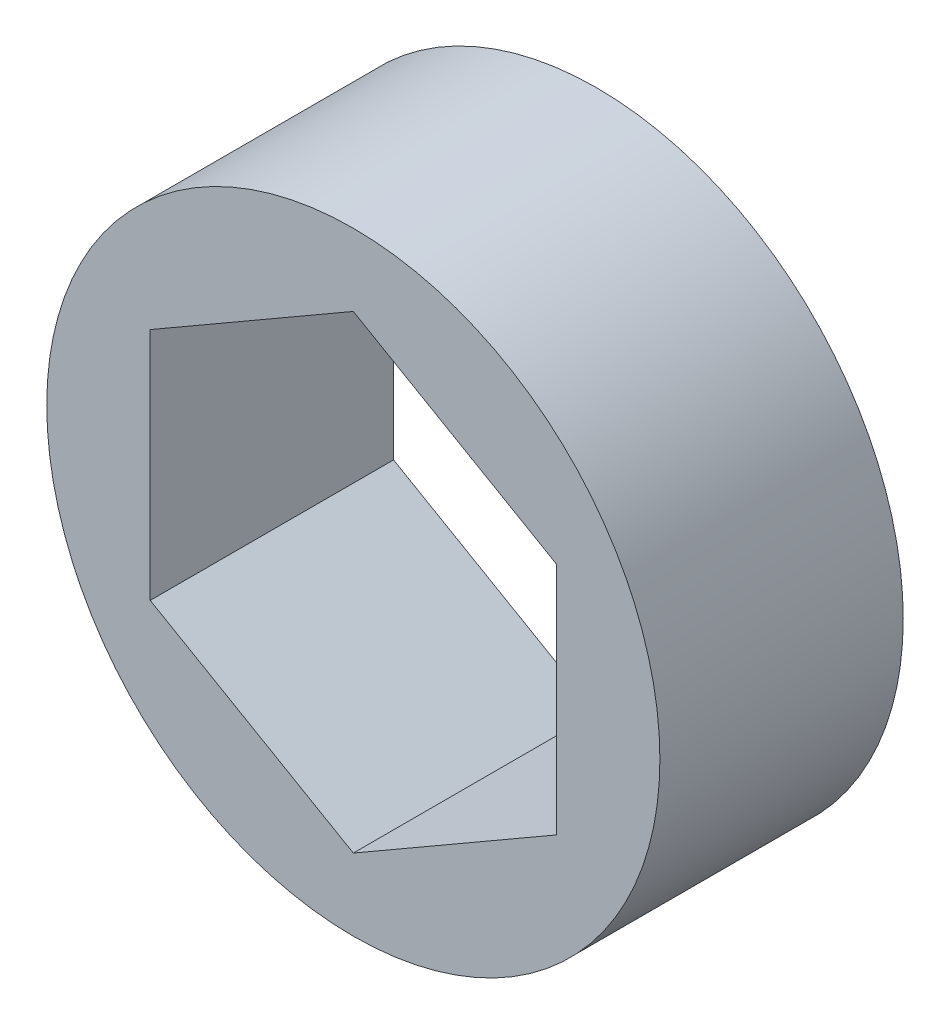
SolidWorks part; units mm, degrees
material "Nylon 101"
ref_plane "Front Plane" through (0, 0, 0) normal (0, 0, 1) x (1, 0, 0)
ref_plane "Top Plane" through (0, 0, 0) normal (0, 1, 0) x (1, 0, 0)
ref_plane "Right Plane" through (0, 0, 0) normal (1, 0, 0) x (0, 0, -1)
sketch "Sketch1" plane through (0, 0, 0) normal (0, 0, 1) x (1, 0, 0)
  line L1 (6.731, 3.8861) -> (0, 7.7723)
  line L2 (0, 7.7723) -> (-6.731, 3.8861)
  line L3 (-6.731, 3.8861) -> (-6.731, -3.8861)
  line L4 (-6.731, -3.8861) -> (0, -7.7723)
  line L5 (0, -7.7723) -> (6.731, -3.8861)
  line L6 (6.731, -3.8861) -> (6.731, 3.8861)
  circle A0 centre (0, 0) radius 6.731 construction
  circle A1 centre (0, 0) radius 10.16
  dimension "D1" = 13.462
  dimension "D2" = 20.32
extrude "Boss-Extrude1" add sketch "Sketch1" along normal blind 8.0645
